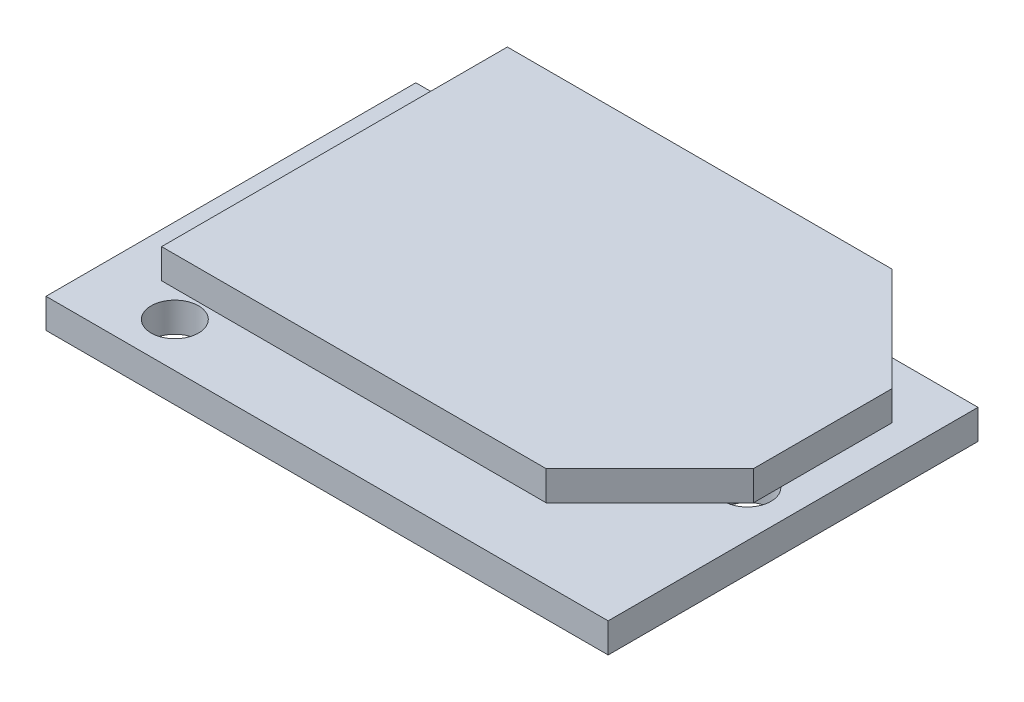
SolidWorks part; units mm, degrees
ref_plane "Ebene vorne" through (0, 0, 0) normal (0, 0, 1) x (1, 0, 0)
ref_plane "Ebene oben" through (0, 0, 0) normal (0, 1, 0) x (1, 0, 0)
ref_plane "Ebene rechts" through (0, 0, 0) normal (1, 0, 0) x (0, 0, -1)
sketch "Sketch1" plane through (0, 0, 0) normal (0, 1, 0) x (1, 0, 0)
  line L0 (-10.3687, 0) -> (25.2304, 0) construction
  line L2 (0, 12.5) -> (38, 12.5)
  line L3 (0, 12.5) -> (0, -12.5)
  line L4 (0, -12.5) -> (38, -12.5)
  line L5 (38, 12.5) -> (38, -12.5)
  circle A0 centre (5.71, 9.5) radius 1.6
  circle A1 centre (5.71, -9.5) radius 1.6
  circle A2 centre (34.91, 0) radius 1.6
  dimension "D4" = 3.2
  dimension "D5" = 3.2
  dimension "D1" = 25
  dimension "D2" = 38
  dimension "D3" = 19
  dimension "D6" = 5.71
  dimension "D7" = 29.2
extrude "Boss-Extrude1" add sketch "Sketch1" along normal blind 2
sketch "Sketch2" plane through (0, 0, 0) normal (0, 1, 0) x (1, 0, 0)
  line L0 (33, -11.6864) -> (40, -4.6864)
  line L1 (7, 11.6864) -> (33, 11.6864)
  line L2 (7, 11.6864) -> (7, -11.6864)
  line L3 (7, -11.6864) -> (33, -11.6864)
  line L4 (3.4909, 0) -> (48.4454, 0) construction
  line L5 (40, -4.6864) -> (40, 4.6864)
  line L6 (40, 4.6864) -> (33, 11.6864)
  line L7 (0, 12.5) -> (0, -12.5) construction
  line L8 (38, -12.5) -> (38, 12.5) construction
  dimension "D1" = 45
  dimension "D2" = 26
  dimension "D3" = 7
  dimension "D4" = 2
  dimension "D5" = 45
extrude "Boss-Extrude2" add sketch "Sketch2" along normal blind 2 from offset 6 separate body
